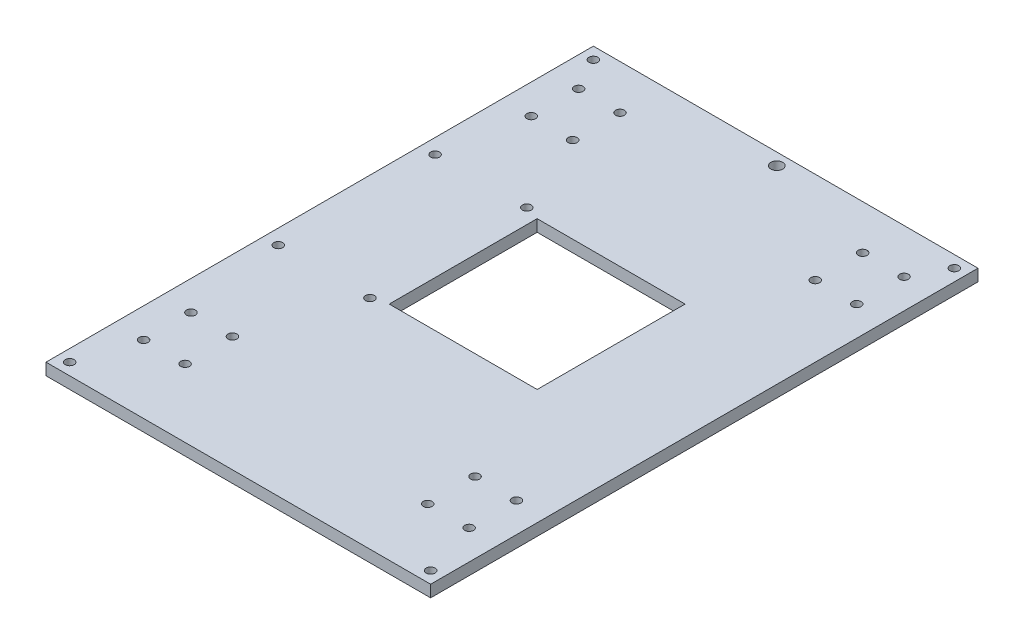
SolidWorks part; units mm, degrees
ref_plane "Front Plane" through (0, 0, 0) normal (0, 0, 1) x (1, 0, 0)
ref_plane "Top Plane" through (0, 0, 0) normal (0, 1, 0) x (1, 0, 0)
ref_plane "Right Plane" through (0, 0, 0) normal (1, 0, 0) x (0, 0, -1)
sketch "Sketch1" plane through (0, 0, 0) normal (0, 1, 0) x (1, 0, 0)
  line L0 (65, 182.3693) -> (65, -110.8281) construction
  line L1 (0, 0) -> (130, 0)
  line L2 (0, 0) -> (0, 185)
  line L3 (0, 185) -> (130, 185)
  line L4 (130, 0) -> (130, 185)
  line L5 (-66.1733, 96.5) -> (261.914, 96.5) construction
  circle A8 centre (10, 39) radius 1.5
  circle A9 centre (24, 39) radius 1.5
  circle A10 centre (10, 23) radius 1.5
  circle A11 centre (24, 23) radius 1.5
  circle A12 centre (120, 23) radius 1.5
  circle A13 centre (120, 39) radius 1.5
  circle A14 centre (106, 39) radius 1.5
  circle A15 centre (106, 23) radius 1.5
  circle A16 centre (106, 170) radius 1.5
  circle A17 centre (120, 170) radius 1.5
  circle A18 centre (106, 154) radius 1.5
  circle A19 centre (120, 154) radius 1.5
  circle A20 centre (24, 154) radius 1.5
  circle A21 centre (24, 170) radius 1.5
  circle A22 centre (10, 170) radius 1.5
  circle A23 centre (10, 154) radius 1.5
  dimension "D3" = 3
  dimension "D4" = 14
  dimension "D5" = 14
  dimension "D6" = 16
  dimension "D7" = 23
  dimension "D8" = 16
  dimension "D9" = 10
  dimension "D10" = 23
  dimension "D11" = 39
  dimension "D12" = 24
  dimension "D13" = 15
  dimension "D1" = 185
  dimension "D2" = 130
extrude "Boss-Extrude1" add sketch "Sketch1" along normal blind 4
sketch "Sketch2" plane through (0, 4, 0) normal (0, 1, 0) x (1, 0, 0)
  line L1 (41, 125) -> (91, 125)
  line L2 (41, 125) -> (41, 75)
  line L3 (41, 75) -> (91, 75)
  line L4 (91, 125) -> (91, 75)
  line L5 (41, 125) -> (91, 75) construction
  line L6 (41, 75) -> (91, 125) construction
  line L8 (0, 0) -> (130, 0) construction
  line L9 (130, 0) -> (130, 185) construction
  point P0 (66, 100)
  dimension "D1" = 50
  dimension "D2" = 50
  dimension "D3" = 75
  dimension "D4" = 39
extrude "Cut-Extrude1" cut sketch "Sketch2" against normal blind 4
sketch "Sketch3" plane through (0, 4, 0) normal (0, 1, 0) x (1, 0, 0)
  line L0 (0, 0) -> (130, 0) construction
  line L5 (130, 0) -> (130, 185) construction
  line L6 (0, 185) -> (0, 0) construction
  line L7 (130, 185) -> (0, 185) construction
  circle A1 centre (126, 4) radius 1.5
  circle A2 centre (126, 181) radius 1.5
  circle A3 centre (4, 4) radius 1.5
  circle A4 centre (4, 181) radius 1.5
  circle A9 centre (63, 181) radius 2
  dimension "D6" = 59
  dimension "D8" = 4
  dimension "D9" = 4
  dimension "D10" = 3
  dimension "D23" = 4
  dimension "D24" = 4
  dimension "D25" = 3
  dimension "D26" = 4
  dimension "D27" = 4
  dimension "D28" = 3
  dimension "D29" = 4
  dimension "D30" = 4
  dimension "D31" = 3
  dimension "D4" = 4
  dimension "D5" = 63
extrude "Cut-Extrude2" cut sketch "Sketch3" against normal blind 49.5
sketch "Sketch4" plane through (0, 4, 0) normal (0, 1, 0) x (1, 0, 0)
  line L1 (130, 0) -> (130, 185) construction
  line L2 (0, 92.5) -> (130, 92.5) construction
  line L3 (0, 185) -> (0, 0) construction
  line L4 (130, 185) -> (0, 185) construction
  circle A1 centre (66, 181) radius 2
  circle A3 centre (126, 181) radius 1.5 construction
  point P0 (65.2783, 180.4974)
  dimension "D1" = 4
  dimension "D2" = 4
  dimension "D3" = 60
extrude "Cut-Extrude3" cut sketch "Sketch4" against normal blind 49.5
sketch "Sketch5" plane through (0, 4, 0) normal (0, 1, 0) x (1, 0, 0)
  line L6 (20.5, 130) -> (20.5, 70) construction
  line L7 (2.5, 100) -> (38.5, 100) construction
  line L8 (0, 185) -> (0, 0) construction
  line L10 (130, 185) -> (0, 185) construction
  circle A0 centre (5, 126.5) radius 1.5
  circle A1 centre (5, 73.5) radius 1.5
  circle A2 centre (36, 126.5) radius 1.5
  circle A3 centre (36, 73.5) radius 1.5
  point P18 (0, 0)
  dimension "D5" = 3
  dimension "D1" = 5
  dimension "D2" = 58.5
  dimension "D3" = 53
  dimension "D4" = 31
extrude "Cut-Extrude5" cut sketch "Sketch5" against normal blind 10
